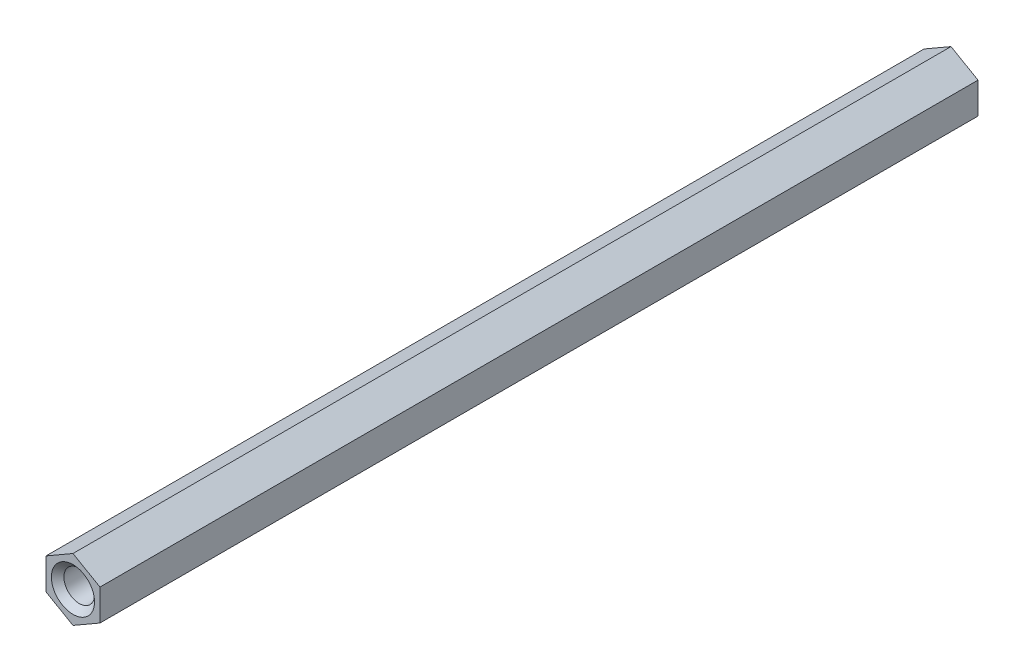
SolidWorks part; units mm, degrees
ref_plane "Front Plane" through (0, 0, 0) normal (0, 0, 1) x (1, 0, 0)
ref_plane "Top Plane" through (0, 0, 0) normal (0, 1, 0) x (1, 0, 0)
ref_plane "Right Plane" through (0, 0, 0) normal (1, 0, 0) x (0, 0, -1)
sketch "Sketch1" plane through (0, 0, 0) normal (0, 0, 1) x (1, 0, 0)
  line L0 (-4.7625, 0) -> (4.7625, 0) construction
  line L9 (0, 5.4993) -> (-4.7625, 2.7496) construction
  line L10 (-4.7625, 2.7496) -> (-4.7625, -2.7496) construction
  line L11 (-4.7625, -2.7496) -> (0, -5.4993) construction
  line L12 (0, -5.4993) -> (4.7625, -2.7496) construction
  line L13 (4.7625, -2.7496) -> (4.7625, 2.7496) construction
  line L14 (4.7625, 2.7496) -> (0, 5.4993) construction
  circle A3 centre (0, 0) radius 4.7625 construction
  point P4 (0, 0)
  dimension "Width" = 9.525
sketch "Sketch2" plane through (0, 0, 0) normal (1, 0, 0) x (0, 0, -1)
  line L0 (77.5, 5.4993) -> (-77.5, 5.4993) construction
  point P3 (-66.5463, 5.4993)
  point P4 (0, 5.4993)
  point P5 (66.5463, 5.4993)
  dimension "Length" = 155
  dimension "D1" = 10.9537
  dimension "D2" = 10.9537
sketch "Sketch3" plane through (0, 0, 0) normal (0, 0, 1) x (1, 0, 0)
  line L1 (0, 5.4993) -> (4.7625, 2.7496)
  line L2 (4.7625, 2.7496) -> (4.7625, -2.7496)
  line L3 (4.7625, -2.7496) -> (0, -5.4993)
  line L4 (0, -5.4993) -> (-4.7625, -2.7496)
  line L5 (-4.7625, -2.7496) -> (-4.7625, 2.7496)
  line L6 (-4.7625, 2.7496) -> (0, 5.4993)
extrude "Boss-Extrude1" add sketch "Sketch3" along normal mid plane 155
sketch "Sketch6" plane through (0, 0, 77.5) normal (0, 0, 1) x (1, 0, 0)
  point P0 (0, 0)
hole_wizard "1/4-28 Tapped Hole1" positions "Sketch6" profile "Sketch5" tap size "1/4-28" standard "ANSI Inch"
sketch "Sketch5" plane through (0, 0, 77.5) normal (1, 0, 0) x (0, -1, 0)
  line L0 (0, 0) -> (0, 16.8654)
  line L1 (0, 16.8654) -> (2.7051, 15.24)
  line L2 (2.7051, 15.24) -> (2.7051, 1.1049)
  line L3 (2.7051, 1.1049) -> (3.81, 0)
  line L5 (3.81, 0) -> (0, 0)
  line L6 (-2.7051, 1.1049) -> (-3.81, 0) construction
  line L10 (0, 16.8654) -> (-2.7051, 15.24) construction
  line L11 (0, -6.35) -> (0, 107.95) construction
  dimension "Tap Drill Dia." = 5.4102
  dimension "Tap Drill Depth" = 15.24
  dimension "Near C'Sink Dia." = 7.62
  dimension "Near C'Sink Angle" = 90
  dimension "Drill Angle" = 118
cosmetic thread "Hole Thread1"
sketch "Sketch9" plane through (0, 0, -77.5) normal (0, 0, -1) x (-1, 0, 0)
  point P0 (0, 0)
hole_wizard "1/4-28 Tapped Hole2" positions "Sketch9" profile "Sketch8" tap size "1/4-28" standard "ANSI Inch"
cosmetic thread "Hole Thread2"
sketch "Sketch8" plane through (0, 0, -77.5) normal (1, 0, 0) x (0, 1, 0)
  line L0 (0, 0) -> (0, 18.8593)
  line L1 (0, 18.8593) -> (2.7051, 17.2339)
  line L2 (2.7051, 17.2339) -> (2.7051, 1.1049)
  line L3 (2.7051, 1.1049) -> (3.81, 0)
  line L5 (3.81, 0) -> (0, 0)
  line L6 (-2.7051, 1.1049) -> (-3.81, 0) construction
  line L10 (0, 18.8593) -> (-2.7051, 17.2339) construction
  line L11 (0, -6.35) -> (0, 107.95) construction
  dimension "Tap Drill Dia." = 5.4102
  dimension "Tap Drill Depth" = 17.2339
  dimension "Near C'Sink Dia." = 7.62
  dimension "Near C'Sink Angle" = 90
  dimension "Drill Angle" = 118
equation "\"D1@Boss-Extrude1\" = \"Length@Sketch2\""
equation "\"D1@Sketch2\" = \"Width@Sketch1\" * 1.15"
equation "\"D2@Sketch2\"=\"D1@Sketch2\""
